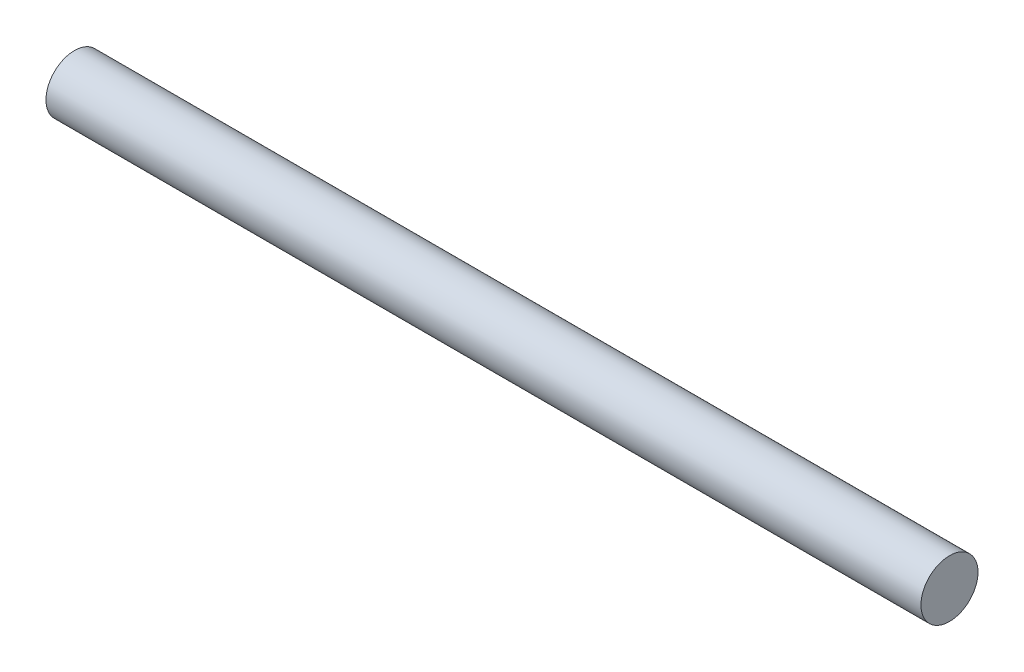
SolidWorks part; units mm, degrees
material "Stainless Steel (ferritic)"
ref_plane "Front Plane" through (0, 0, 0) normal (0, 0, 1) x (1, 0, 0)
ref_plane "Top Plane" through (0, 0, 0) normal (0, 1, 0) x (1, 0, 0)
ref_plane "Right Plane" through (0, 0, 0) normal (1, 0, 0) x (0, 0, -1)
sketch "Sketch1" plane through (0, 0, 0) normal (1, 0, 0) x (0, 0, -1)
  circle A0 centre (0, 0) radius 1.5
  dimension "D1" = 3
extrude "Boss-Extrude1" add sketch "Sketch1" along normal blind 46 contours A0
